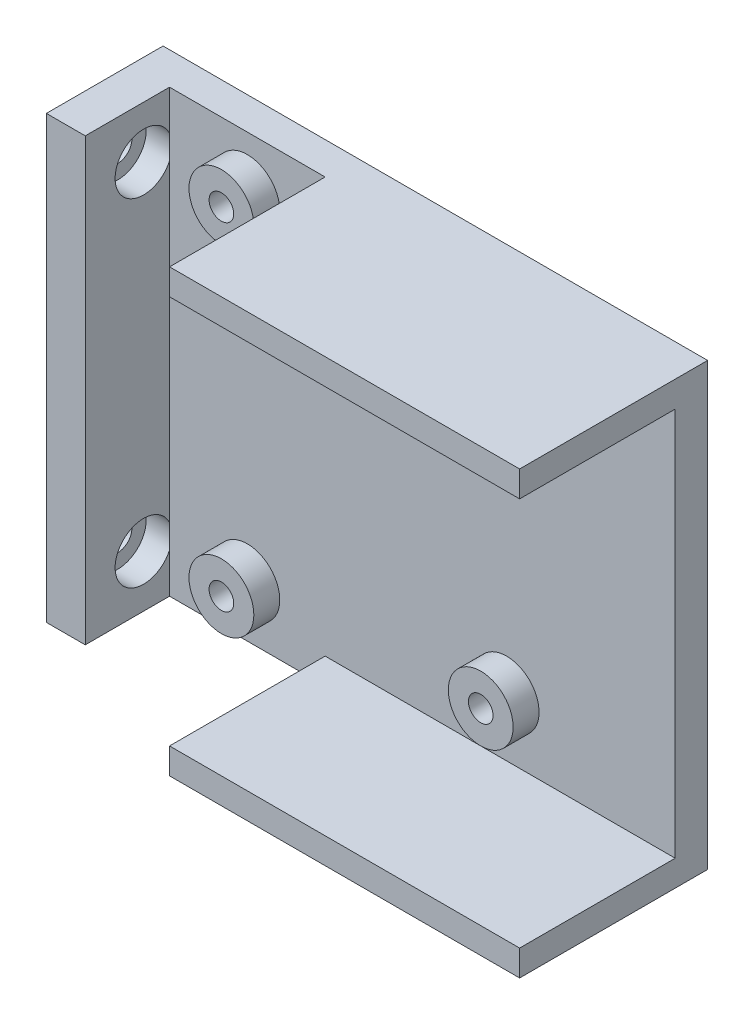
SolidWorks part; units mm, degrees
ref_plane "Front Plane" through (0, 0, 0) normal (0, 0, 1) x (1, 0, 0)
ref_plane "Top Plane" through (0, 0, 0) normal (0, 1, 0) x (1, 0, 0)
ref_plane "Right Plane" through (0, 0, 0) normal (1, 0, 0) x (0, 0, -1)
sketch "Sketch1" plane through (0, 0, 0) normal (0, 0, 1) x (1, 0, 0)
  line L1 (0, 0) -> (42, 0)
  line L2 (0, 0) -> (0, 34)
  line L3 (0, 34) -> (42, 34)
  line L4 (42, 0) -> (42, 34)
  dimension "D1" = 42
  dimension "D2" = 34
extrude "Boss-Extrude1" add sketch "Sketch1" along normal blind 2.5
sketch "Sketch2" plane through (0, 0, 2.5) normal (0, 0, 1) x (1, 0, 0)
  line L0 (0, 34) -> (42, 34)
  line L1 (42, 34) -> (42, 32)
  line L2 (42, 0) -> (42, 34) construction
  line L3 (42, 32) -> (3, 32)
  line L4 (3, 32) -> (3, 2)
  line L5 (3, 2) -> (42, 2)
  line L6 (42, 2) -> (42, 0)
  line L7 (42, 0) -> (0, 0)
  line L8 (0, 0) -> (0, 34)
  dimension "D1" = 2
  dimension "D2" = 2
  dimension "D3" = 3
extrude "Boss-Extrude2" add sketch "Sketch2" along normal blind 12
sketch "Sketch3" plane through (0, 0, 14.5) normal (0, 0, 1) x (1, 0, 0)
  line L0 (0, 0) -> (42, 0) construction
  line L1 (3, 0) -> (15, 0)
  line L2 (3, 0) -> (3, 34)
  line L3 (3, 34) -> (15, 34)
  line L4 (15, 0) -> (15, 34)
  line L5 (42, 34) -> (0, 34) construction
  line L6 (3, 2) -> (3, 32) construction
  dimension "D1" = 12
extrude "Cut-Extrude1" cut sketch "Sketch3" against normal up to surface (12 mm away) up to face at (22.5, 17, 2.5)
hole_wizard "CBORE for M2 SHCS1" positions "Sketch4" profile "Sketch5" counterbore size "M2" standard "ANSI Metric"
sketch "Sketch4" plane through (3, 0, 0) normal (1, 0, 0) x (0, 0, -1)
  line L0 (-14.5, 17) -> (-4.5, 17) construction
  line L1 (-14.5, 0) -> (-14.5, 34) construction
  line L2 (-4.5, 17) -> (-4.5, 30) construction
  line L3 (0, 0) -> (0, 34) construction
  point P6 (-4.5, 30)
  point P13 (0, 0)
  point P14 (-4.5, 4)
  dimension "D1" = 4.5
  dimension "D2" = 13
sketch "Sketch5" plane through (3, 4, 4.5) normal (0, 1, 0) x (0, 0, -1)
  line L0 (0, 0) -> (0, 3)
  line L1 (0, 3) -> (1.1, 3)
  line L3 (1.1, 3) -> (1.1, 2)
  line L4 (1.1, 2) -> (2.2, 2)
  line L5 (2.2, 2) -> (2.2, 0)
  line L7 (2.2, 0) -> (0, 0)
  line L11 (0, -6.35) -> (0, 107.95) construction
  dimension "Thru Hole Dia." = 2.2
  dimension "Thru Hole Depth" = 3
  dimension "C'Bore Dia." = 4.4
  dimension "C'Bore Depth" = 2
sketch "Sketch8" plane through (0, 0, 14.5) normal (0, 0, 1) x (1, 0, 0)
  line L4 (0, 0) -> (3, 0)
  line L5 (3, 0) -> (3, 34)
  line L6 (3, 34) -> (0, 34)
  line L7 (0, 34) -> (0, 0)
  line L8 (0, 0) -> (3, 0)
  line L9 (3, 0) -> (3, 34)
  line L10 (3, 34) -> (0, 34)
  line L11 (0, 34) -> (0, 0)
  dimension "D1" = 0
extrude "Cut-Extrude2" cut sketch "Sketch8" against normal offset from surface (5.5 mm away) 9 up to face at (21, 17, 0)
sketch "Sketch9" plane through (0, 0, 2.5) normal (0, 0, 1) x (1, 0, 0)
  line L0 (9, 34) -> (9, 0) construction
  line L1 (15, 34) -> (3, 34) construction
  line L2 (3, 0) -> (15, 0) construction
  line L3 (42, 17) -> (29, 17) construction
  line L4 (42, 2) -> (42, 32) construction
  line L5 (29, 17) -> (29, 27.5) construction
  circle A0 centre (9, 30) radius 2.5
  circle A1 centre (9, 4) radius 2.5
  circle A2 centre (29, 27.5) radius 2.5
  circle A3 centre (29, 6.5) radius 2.5
  point P10 (9, 17)
  dimension "D3" = 5
  dimension "D4" = 5
  dimension "D1" = 13
  dimension "D2" = 13
  dimension "D5" = 13
  dimension "D6" = 10.5
extrude "Boss-Extrude3" add sketch "Sketch9" along normal blind 2 contours A1 | A0
sketch "Sketch10" plane through (0, 0, 4.5) normal (0, 0, 1) x (1, 0, 0)
  circle A0 centre (9, 30) radius 0.95
  circle A1 centre (9, 4) radius 0.95
  circle A2 centre (29, 27.5) radius 0.95
  circle A3 centre (29, 6.5) radius 0.95
  dimension "D1" = 1.9
extrude "Cut-Extrude3" cut sketch "Sketch10" against normal up to surface (4.5 mm away) up to face at (21, 17, 0)
